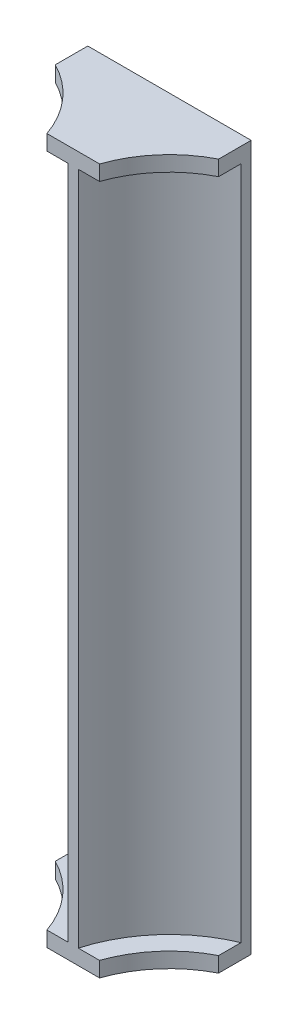
SolidWorks part; units mm, degrees
ref_plane "前视基准面" through (0, 0, 0) normal (0, 0, 1) x (1, 0, 0)
ref_plane "上视基准面" through (0, 0, 0) normal (0, 1, 0) x (1, 0, 0)
ref_plane "右视基准面" through (0, 0, 0) normal (1, 0, 0) x (0, 0, -1)
sketch "草图1" plane through (0, 0, 0) normal (0, 1, 0) x (1, 0, 0)
  line L0 (12.55, 3.5777) -> (13.55, 3.5777)
  line L1 (5.01, 13.05) -> (21.09, 13.05)
  line L2 (5.01, 12.05) -> (5.01, 13.05)
  line L3 (21.09, 12.05) -> (21.09, 13.05)
  arc A0 (12.55, 3.5777) -> (5.01, 12.05) centre (0, 0) ccw
  arc A1 (21.09, 12.05) -> (13.55, 3.5777) centre (26.1, 0) ccw
  point P13 (18.1962, 10.3843)
  point P14 (18.5549, 10.6477)
  point P15 (13.05, 0)
  point P16 (13.05, 6.9839)
  point P17 (13.05, 13.05)
  point P18 (13.05, 13.05)
  point P19 (17.3479, 13.05)
  point P20 (17.2697, 9.6088)
  dimension "D1" = 26.1
  dimension "D2" = 1
  dimension "D3" = 1
extrude "凸台-拉伸1" add sketch "草图1" along normal blind 66.4
sketch "草图2" plane through (0, 66.4, 0) normal (0, 1, 0) x (1, 0, 0)
  line L0 (5.01, 13.05) -> (5.01, 9.849)
  line L1 (10.4548, 3.5777) -> (15.6452, 3.5777)
  line L2 (13.05, 13.05) -> (13.05, 1.3129) construction
  line L3 (21.09, 13.05) -> (5.01, 13.05) construction
  line L4 (21.09, 9.849) -> (21.09, 13.05)
  line L5 (21.09, 13.05) -> (5.01, 13.05)
  arc A0 (15.6452, 3.5777) -> (21.09, 9.849) centre (26.1, 0) cw
  arc A2 (10.6266, 3.0294) -> (4.2422, 10.2033) centre (0, 0) ccw
  arc A3 (10.4548, 3.5777) -> (5.01, 9.849) centre (0, 0) ccw
  point P7 (0, 0)
  point P20 (5.01, 12.8877)
  dimension "D1" = 2
extrude "凸台-拉伸2" add sketch "草图2" along normal blind 1.5
sketch "草图3" plane through (0, 0, 0) normal (0, -1, 0) x (1, 0, 0)
  line L0 (10.4548, -3.5777) -> (15.6452, -3.5777)
  line L1 (5.01, -9.849) -> (5.01, -13.05)
  line L2 (5.01, -13.05) -> (21.09, -13.05)
  line L3 (21.09, -13.05) -> (21.09, -9.849)
  arc A0 (5.01, -9.849) -> (10.4548, -3.5777) centre (0, 0) ccw construction
  arc A1 (5.01, -9.849) -> (10.4548, -3.5777) centre (0, 0) ccw
  arc A2 (15.6452, -3.5777) -> (21.09, -9.849) centre (26.1, 0) ccw
  arc A3 (10.4548, -3.5777) -> (5.01, -9.849) centre (0, 0) cw
  point P9 (5.01, -9.849)
  arc M2 (12.55, -3.5777) -> (5.01, -12.05) centre (0, 0) cw
  line M3 (5.01, -12.05) -> (5.01, -13.05)
  line M4 (5.01, -13.05) -> (21.09, -13.05)
  line M5 (21.09, -13.05) -> (21.09, -12.05)
  arc M6 (21.09, -12.05) -> (13.55, -3.5777) centre (26.1, 0) cw
  line M7 (13.55, -3.5777) -> (12.55, -3.5777)
extrude "凸台-拉伸3" add sketch "草图3" along normal blind 1.5 contours A1 L1 L0 M2 | M7 M2 M3 M4 M5 M6 | A2 L0 L3 M6
